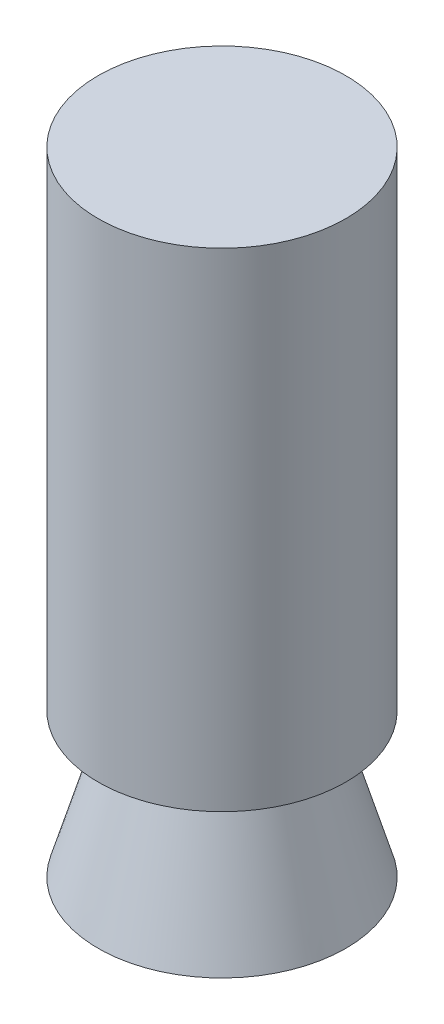
SolidWorks part; units mm, degrees
ref_plane "Plan de face" through (0, 0, 0) normal (0, 0, 1) x (1, 0, 0)
ref_plane "Plan de dessus" through (0, 0, 0) normal (0, 1, 0) x (1, 0, 0)
ref_plane "Plan de droite" through (0, 0, 0) normal (1, 0, 0) x (0, 0, -1)
sketch "Esquisse1" plane through (0, 0, 0) normal (0, 0, 1) x (1, 0, 0)
  line L0 (-6.6325, 74.8573) -> (-45.6325, 74.8573)
  line L1 (-45.6325, 74.8573) -> (-45.6325, -98.1793)
  line L2 (-45.6325, -98.1793) -> (-25.4465, -98.1793)
  line L3 (-25.4465, -98.1793) -> (-42.2554, -155.1427)
  line L5 (-6.6325, 84.8573) -> (-55.6325, 84.8573)
  line L6 (-55.6325, 84.8573) -> (-55.6325, -108.1793)
  line L7 (-55.6325, -108.1793) -> (-38.8236, -108.1793)
  line L8 (-38.8236, -108.1793) -> (-55.6325, -165.1427)
  line L9 (-55.6325, -165.1427) -> (-45.2062, -165.1427)
  line L10 (-6.6325, 84.8573) -> (-6.6325, 74.8573)
  line L11 (-42.2554, -155.1427) -> (-45.2062, -165.1427)
  line L12 (-55.6325, -165.1427) -> (-6.6325, -165.1427) construction
  line L13 (-42.2554, -155.1427) -> (-6.6325, -155.1427) construction
  point P12 (-35.21, -108.1793)
  point P14 (-55.6325, -165.1427)
  dimension "D2" = 49
  dimension "D3" = 250
  dimension "D1" = 10
revolve "Révolution1" add sketch "Esquisse1" angle 360 about L10
